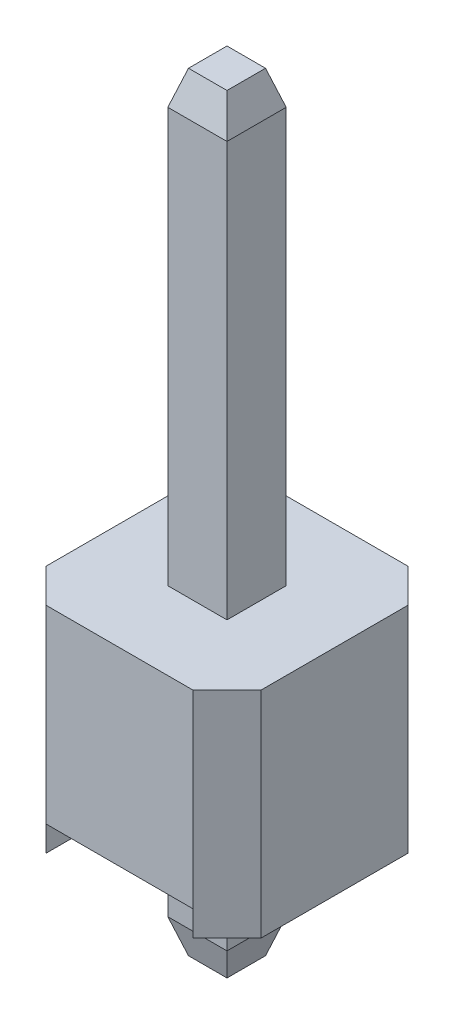
SolidWorks part; units mm, degrees
ref_plane "Front Plane" through (0, 0, 0) normal (0, 0, 1) x (1, 0, 0)
ref_plane "Top Plane" through (0, 0, 0) normal (0, 1, 0) x (1, 0, 0)
ref_plane "Right Plane" through (0, 0, 0) normal (1, 0, 0) x (0, 0, -1)
sketch "Sketch1" plane through (0, 0, 0) normal (0, 1, 0) x (1, 0, 0)
  line L1 (-1.27, 1.27) -> (1.27, 1.27)
  line L2 (-1.27, 1.27) -> (-1.27, -1.27)
  line L3 (-1.27, -1.27) -> (1.27, -1.27)
  line L4 (1.27, 1.27) -> (1.27, -1.27)
  line L5 (-1.27, 1.27) -> (1.27, -1.27) construction
  line L6 (-1.27, -1.27) -> (1.27, 1.27) construction
  point P0 (0, 0)
  dimension "D1" = 2.54
  dimension "D2" = 2.54
extrude "Boss-Extrude1" add sketch "Sketch1" along normal blind 2.54
chamfer "Chamfer1" distance 0.4 angle 45 4 edges at (-1.27, 1.27, -1.27) (1.27, 1.27, -1.27) (-1.27, 1.27, 1.27) (1.27, 1.27, 1.27)
sketch "Sketch2" plane through (0, 0, 0) normal (0, -1, 0) x (1, 0, 0)
  line L1 (-0.87, 1.27) -> (0.87, 1.27)
  line L2 (-0.87, 1.27) -> (-0.87, -1.27)
  line L3 (-0.87, -1.27) -> (0.87, -1.27)
  line L4 (0.87, 1.27) -> (0.87, -1.27)
extrude "Cut-Extrude1" cut sketch "Sketch2" against normal blind 0.3
sketch "Sketch3" plane through (0, 2.54, 0) normal (0, 1, 0) x (1, 0, 0)
  line L1 (0.35, 0.35) -> (-0.35, 0.35)
  line L2 (0.35, 0.35) -> (0.35, -0.35)
  line L3 (0.35, -0.35) -> (-0.35, -0.35)
  line L4 (-0.35, 0.35) -> (-0.35, -0.35)
  line L5 (0.35, 0.35) -> (-0.35, -0.35) construction
  line L6 (0.35, -0.35) -> (-0.35, 0.35) construction
  point P0 (0, 0)
  dimension "D1" = 0.7
  dimension "D2" = 0.7
extrude "Boss-Extrude2" add sketch "Sketch3" along normal blind 5.3
sketch "Sketch4" plane through (0, 0.3, 0) normal (0, -1, 0) x (1, 0, 0)
  line L0 (-0.35, 0.35) -> (0.35, 0.35) construction
  line L1 (-0.35, 0.35) -> (0.35, 0.35)
  line L2 (-0.35, 0.35) -> (-0.35, -0.35)
  line L3 (-0.35, -0.35) -> (0.35, -0.35)
  line L4 (0.35, 0.35) -> (0.35, -0.35)
  line L5 (-0.35, 0.35) -> (0.35, -0.35) construction
  line L6 (-0.35, -0.35) -> (0.35, 0.35) construction
  line L7 (0.35, 0.35) -> (0.35, -0.35) construction
  point P0 (0, 0)
extrude "Boss-Extrude3" add sketch "Sketch4" along normal blind 1.55
chamfer "Chamfer2" distance 0.4 angle 17 8 edges at (0, 7.84, -0.35) (-0.35, 7.84, 0) (0.35, 7.84, 0) (0, 7.84, 0.35) (0, -1.25, -0.35) (-0.35, -1.25, 0) (0.35, -1.25, 0) (0, -1.25, 0.35)
